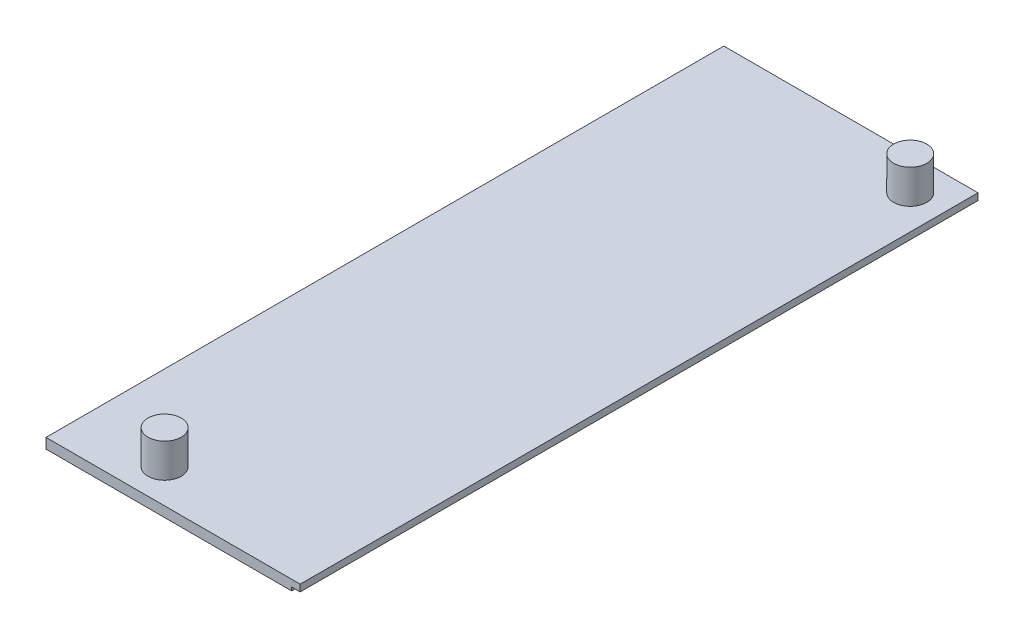
SolidWorks part; units mm, degrees
ref_plane "Front Plane" through (0, 0, 0) normal (0, 0, 1) x (1, 0, 0)
ref_plane "Top Plane" through (0, 0, 0) normal (0, 1, 0) x (1, 0, 0)
ref_plane "Right Plane" through (0, 0, 0) normal (1, 0, 0) x (0, 0, -1)
sketch "Sketch1" plane through (0, 0, 0) normal (0, 0, 1) x (1, 0, 0)
  line L1 (0, 0) -> (75, 0)
  line L2 (0, 0) -> (0, 3)
  line L3 (0, 3) -> (75, 3)
  line L4 (75, 0) -> (75, 3)
  dimension "D1" = 3
  dimension "D2" = 75
extrude "Boss-Extrude1" add sketch "Sketch1" along normal blind 200
sketch "Sketch2" plane through (0, 3, 0) normal (0, 1, 0) x (1, 0, 0)
  line L1 (187.5, 0) -> (-37.5, 0)
  line L2 (187.5, 0) -> (187.5, -200)
  line L3 (187.5, -200) -> (-37.5, -200)
  line L4 (-37.5, 0) -> (-37.5, -200)
  line L5 (175, -200) -> (-25, -200)
  line L6 (175, -200) -> (175, 0)
  line L7 (175, 0) -> (-25, 0)
  line L8 (-25, -200) -> (-25, 0)
  line L9 (75, -200) -> (0, -200) construction
  line L10 (75, 0) -> (0, 0) construction
  line L11 (75, -200) -> (75, 0) construction
  circle A0 centre (165, -190) radius 4.9
  circle A1 centre (125, -10) radius 4.9
  circle A2 centre (85, -190) radius 4.9
  circle A3 centre (65, -10) radius 4.9
  circle A4 centre (25, -190) radius 4.9
  circle A5 centre (-27.5, -10) radius 4.9
  point P4 (0, 0)
  point P27 (0, 0)
  point P28 (0, 0)
  point P30 (0, 0)
  dimension "D4" = 10
  dimension "D5" = 10
  dimension "D6" = 9.8
  dimension "D7" = 9.8
  dimension "D8" = 10
  dimension "D9" = 40
  dimension "D11" = 10
  dimension "D12" = 10
  dimension "D13" = 80
  dimension "D14" = 40
  dimension "D15" = 10
  dimension "D16" = 10
  dimension "D17" = 60
  dimension "D19" = 9.8
  dimension "D20" = 9.8
  dimension "D21" = 9.8
  dimension "D22" = 9.8
  dimension "D1" = 225
  dimension "D2" = 12.5
  dimension "D3" = 12.5
  dimension "D10" = 100
extrude "Boss-Extrude2" add sketch "Sketch2" along normal blind 10 contours A4 | A3 | A0 | A2 | A5
sketch "Sketch5" plane through (0, 0, 0) normal (0, -1, 0) x (1, 0, 0)
  line L18 (0, 0) -> (75, 0) construction
  line L21 (0, 0) -> (2.5, 0)
  line L24 (75, 200) -> (72.5, 200)
  line L25 (75, 200) -> (75, 0)
  line L26 (75, 0) -> (72.5, 0)
  line L27 (72.5, 200) -> (72.5, 0)
  line M2 (0, 0) -> (75, 0)
  line M3 (75, 0) -> (75, 200)
  line M4 (75, 200) -> (0, 200)
  dimension "D2" = 2.5
extrude "Cut-Extrude2" cut sketch "Sketch5" against normal blind 1 contours L27 M4 M2 M3
